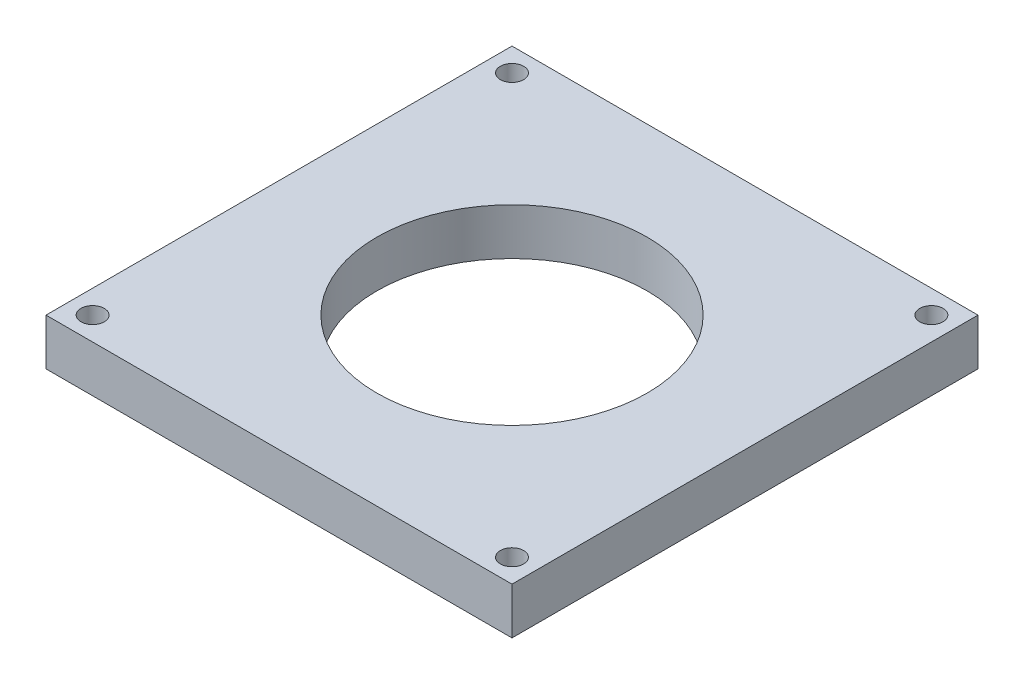
SolidWorks part; units mm, degrees
ref_plane "Front Plane" through (0, 0, 0) normal (0, 0, 1) x (1, 0, 0)
ref_plane "Top Plane" through (0, 0, 0) normal (0, 1, 0) x (1, 0, 0)
ref_plane "Right Plane" through (0, 0, 0) normal (1, 0, 0) x (0, 0, -1)
sketch "Sketch2" plane through (0, 0, 0) normal (0, 1, 0) x (1, 0, 0)
  line L1 (-12.7, -12.7) -> (12.7, -12.7)
  line L2 (-12.7, -12.7) -> (-12.7, 12.7)
  line L3 (-12.7, 12.7) -> (12.7, 12.7)
  line L4 (12.7, -12.7) -> (12.7, 12.7)
  line L5 (-12.7, -12.7) -> (12.7, 12.7) construction
  line L6 (-12.7, 12.7) -> (12.7, -12.7) construction
  circle A0 centre (0, 0) radius 7.366
  circle A1 centre (11.43, 11.43) radius 0.635
  circle A2 centre (11.43, -11.43) radius 0.635
  circle A3 centre (-11.43, -11.43) radius 0.635
  circle A4 centre (-11.43, 11.43) radius 0.635
  point P0 (0, 0)
  point P19 (0, 0)
  dimension "D3" = 14.732
  dimension "D4" = 1.27
  dimension "D5" = 1.27
  dimension "D1" = 25.4
  dimension "D2" = 25.4
  dimension "D6" = 4
extrude "Boss-Extrude3" add sketch "Sketch2" along normal blind 2.54
